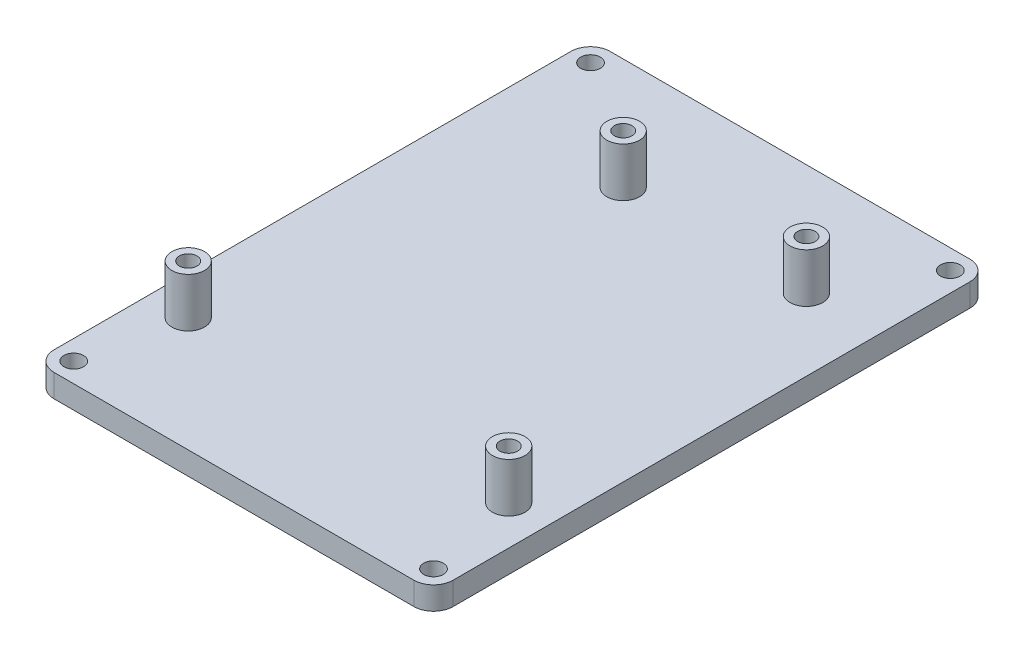
SolidWorks part; units mm, degrees
ref_plane "Front Plane" through (0, 0, 0) normal (0, 0, 1) x (1, 0, 0)
ref_plane "Top Plane" through (0, 0, 0) normal (0, 1, 0) x (1, 0, 0)
ref_plane "Right Plane" through (0, 0, 0) normal (1, 0, 0) x (0, 0, -1)
sketch "Sketch1" plane through (0, 0, 0) normal (0, 1, 0) x (1, 0, 0)
  line L1 (-30.5, 42.5) -> (30.5, 42.5)
  line L2 (-30.5, 42.5) -> (-30.5, -42.5)
  line L3 (-30.5, -42.5) -> (30.5, -42.5)
  line L4 (30.5, 42.5) -> (30.5, -42.5)
  line L5 (-30.5, 42.5) -> (30.5, -42.5) construction
  line L6 (-30.5, -42.5) -> (30.5, 42.5) construction
  point P0 (0, 0)
  dimension "D1" = 61
  dimension "D2" = 85
extrude "Boss-Extrude1" add sketch "Sketch1" along normal blind 3.5
sketch "Sketch2" plane through (0, 3.5, 0) normal (0, 1, 0) x (1, 0, 0)
  line L0 (-30.5, 42.5) -> (-30.5, -42.5) construction
  line L1 (30.5, 42.5) -> (-30.5, 42.5) construction
  line L2 (30.5, -42.5) -> (30.5, 42.5) construction
  line L3 (-30.5, -42.5) -> (30.5, -42.5) construction
  circle A0 centre (-27.5, 39.5) radius 1.5
  circle A1 centre (27.5, 39.5) radius 1.5
  circle A2 centre (-27.5, -39.5) radius 1.5
  circle A3 centre (27.5, -39.5) radius 1.5
  dimension "D1" = 3
  dimension "D3" = 3
  dimension "D4" = 3
  dimension "D2" = 3
extrude "Cut-Extrude1" cut sketch "Sketch2" against normal blind 3.5
sketch "Sketch3" plane through (0, 3.5, 0) normal (0, 1, 0) x (1, 0, 0)
  line L0 (0, 42.5) -> (0, -42.5) construction
  line L1 (30.5, 42.5) -> (-30.5, 42.5) construction
  line L2 (-30.5, -42.5) -> (30.5, -42.5) construction
  circle A0 centre (-24.5, -25) radius 2.5
  circle A1 centre (24.5, -25) radius 2.5
  circle A2 centre (19.5, 25.5) radius 2.5
  circle A3 centre (-8.5, 25.5) radius 2.5
  dimension "D1" = 24.5
  dimension "D3" = 24.5
  dimension "D4" = 50.5
  dimension "D6" = 28
  dimension "D2" = 17.5
  dimension "D5" = 5
extrude "Boss-Extrude2" add sketch "Sketch3" along normal blind 7.5
sketch "Sketch4" plane through (0, 11, 0) normal (0, 1, 0) x (1, 0, 0)
  circle A0 centre (-8.5, 25.5) radius 1.35
  circle A1 centre (19.5, 25.5) radius 1.35
  circle A2 centre (-24.5, -25) radius 1.35
  circle A3 centre (24.5, -25) radius 1.35
extrude "Cut-Extrude2" cut sketch "Sketch4" against normal blind 7.5
fillet "Fillet1" radius 3 4 edges at (-30.5, 1.75, -42.5) (30.5, 1.75, -42.5) (30.5, 1.75, 42.5) (-30.5, 1.75, 42.5)
